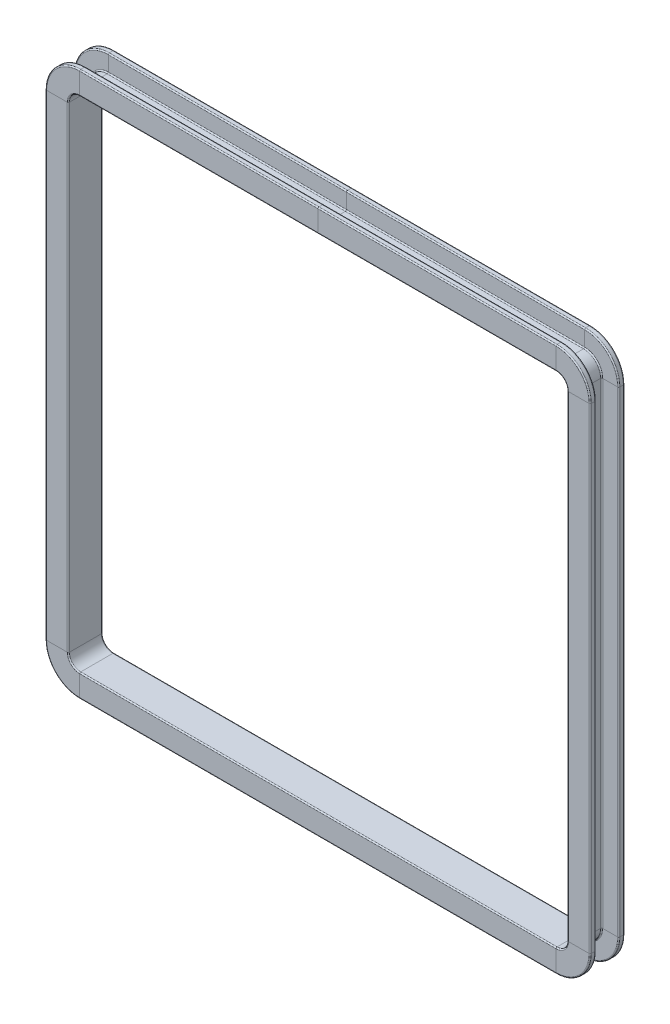
SolidWorks part; units mm, degrees
material "ABS"
ref_plane "Front Plane" through (0, 0, 0) normal (0, 0, 1) x (1, 0, 0)
ref_plane "Top Plane" through (0, 0, 0) normal (0, 1, 0) x (1, 0, 0)
ref_plane "Right Plane" through (0, 0, 0) normal (1, 0, 0) x (0, 0, -1)
sketch "Sketch2" plane through (0, 0, 0) normal (0, 0, 1) x (1, 0, 0)
  line L5 (945.75, 990.75) -> (-945.75, 990.75)
  line L6 (990.75, 945.75) -> (990.75, -945.75)
  line L7 (945.75, -990.75) -> (-945.75, -990.75)
  line L8 (-990.75, 945.75) -> (-990.75, -945.75)
  line L9 (990.75, 990.75) -> (-990.75, -990.75) construction
  line L10 (990.75, -990.75) -> (-990.75, 990.75) construction
  arc A0 (-945.75, -990.75) -> (-990.75, -945.75) centre (-945.75, -945.75) cw
  arc A1 (990.75, -945.75) -> (945.75, -990.75) centre (945.75, -945.75) cw
  arc A2 (945.75, 990.75) -> (990.75, 945.75) centre (945.75, 945.75) cw
  arc A3 (-945.75, 990.75) -> (-990.75, 945.75) centre (-945.75, 945.75) ccw
  point P0 (0, 0)
  point P20 (945.75, 990.75)
  dimension "D2" = 45
  dimension "D1" = 1981.5
sketch "Sketch3" plane through (0, 0, 0) normal (1, 0, 0) x (0, 0, -1)
  line L0 (0, -990.75) -> (0, 990.75) construction
  line L1 (0, 990.75) -> (0, 945.75) construction
  line L2 (-63.525, 990.75) -> (63.525, 990.75)
  line L3 (68.0625, 995.2875) -> (68.0625, 1076.9625)
  line L5 (-45.375, 1076.9625) -> (-45.375, 1017.975)
  line L6 (-40.8375, 1013.4375) -> (40.8375, 1013.4375)
  line L7 (45.375, 1017.975) -> (45.375, 1076.9625)
  line L9 (-68.0625, 1076.9625) -> (-68.0625, 995.2875)
  line L10 (-49.9125, 1081.5) -> (-63.525, 1081.5)
  line L11 (49.9125, 1081.5) -> (63.525, 1081.5)
  arc A0 (-63.525, 990.75) -> (-68.0625, 995.2875) centre (-63.525, 995.2875) cw
  arc A1 (63.525, 990.75) -> (68.0625, 995.2875) centre (63.525, 995.2875) ccw
  arc A2 (68.0625, 1076.9625) -> (63.525, 1081.5) centre (63.525, 1076.9625) ccw
  arc A3 (45.375, 1076.9625) -> (49.9125, 1081.5) centre (49.9125, 1076.9625) cw
  arc A4 (40.8375, 1013.4375) -> (45.375, 1017.975) centre (40.8375, 1017.975) ccw
  arc A5 (-45.375, 1017.975) -> (-40.8375, 1013.4375) centre (-40.8375, 1017.975) ccw
  arc A6 (-49.9125, 1081.5) -> (-45.375, 1076.9625) centre (-49.9125, 1076.9625) cw
  arc A7 (-63.525, 1081.5) -> (-68.0625, 1076.9625) centre (-63.525, 1076.9625) ccw
  point P0 (0, 990.75)
  point P11 (0, 990.75)
  point P23 (68.0625, 990.75)
  point P26 (68.0625, 1081.5)
  point P29 (45.375, 1081.5)
  point P32 (45.375, 1013.4375)
  point P35 (-45.375, 1013.4375)
  dimension "D5" = 4.5375
  dimension "D2" = 22.6875
  dimension "D1" = 90.75
  dimension "D3" = 22.6875
  dimension "D4" = 90.75
sweep "Sweep1" add profiles "Sketch3" path "Sketch2"
sketch "Sketch4" plane through (0, 990.75, 0) normal (0, -1, 0) x (1, 0, 0)
  line L0 (0, -228.5254) -> (0, 308.0042) construction
  line L2 (372.775, -612.4375) -> (372.775, 1259.0625) construction
  circle A0 centre (331.525, 0) radius 25
  circle A1 centre (-331.525, 0) radius 25
  dimension "D1" = 50
  dimension "D2" = 41.25
extrude "Boss-Extrude1" [suppressed] add sketch "Sketch4" along normal blind 30
mirror "Mirror1" [suppressed] about plane through (0, 0, 0) normal (0, 1, 0)
sketch "Sketch5" plane through (-990.75, 0, 0) normal (1, 0, 0) x (0, 0, -1)
  line L0 (531.6875, 383.9) -> (-1178.3125, 383.9) construction
  line L1 (372.4533, 0) -> (-321.9554, 0) construction
  circle A0 centre (0, 342.65) radius 25
  circle A1 centre (0, -342.65) radius 25
  dimension "D1" = 50
  dimension "D2" = 41.25
extrude "Boss-Extrude2" [suppressed] add sketch "Sketch5" along normal blind 30 contours A0 | A1
mirror "Mirror2" [suppressed] about plane through (0, 0, 0) normal (1, 0, 0)
equation "\"A\"= 1.8'Coil Case Length"
equation "\"D2@Sketch2\"=\"A\"/40"
equation "\"B\"= 82.5mm * 1.1'20 AWG Diam*100"
equation "\"D5@Sketch3\"=\"B\"/20"
equation "\"D2@Sketch3\"=\"B\"/4"
equation "\"D1@Sketch3\"=\"B\""
equation "\"D3@Sketch3\"=\"B\"/4"
equation "\"C\"= \"A\" + \"B\" * 2"
equation "\"D1@Sketch2\"=\"C\""
equation "\"D4@Sketch3\"=\"B\""
equation "\"D2@Sketch4\"=\"D\"/2"
equation "\"D\"= 82.5mm"
equation "\"D2@Sketch5\"=\"D\"/2"
